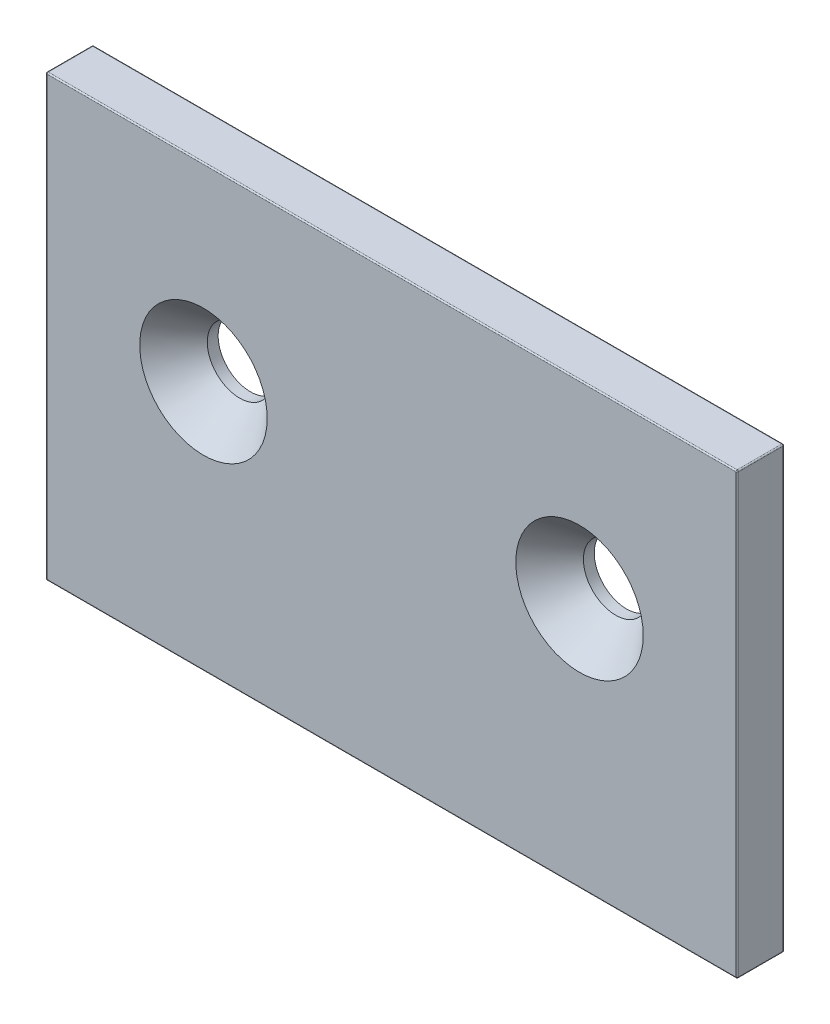
SolidWorks part; units mm, degrees
material "Chrome Stainless Steel"
ref_plane "Front Plane" through (0, 0, 0) normal (0, 0, 1) x (1, 0, 0)
ref_plane "Top Plane" through (0, 0, 0) normal (0, 1, 0) x (1, 0, 0)
ref_plane "Right Plane" through (0, 0, 0) normal (1, 0, 0) x (0, 0, -1)
sketch "Sketch1" plane through (0, 0, 0) normal (0, 0, 1) x (1, 0, 0)
  line L1 (-34.925, 0) -> (34.925, 0)
  line L2 (-34.925, 0) -> (-34.925, 44.45)
  line L3 (-34.925, 44.45) -> (34.925, 44.45)
  line L4 (34.925, 0) -> (34.925, 44.45)
  dimension "D1" = 69.85
  dimension "D2" = 44.45
extrude "Boss-Extrude1" add sketch "Sketch1" along normal mid plane 4.7498
hole_wizard "CSK for 1/4 Flat Head Machine Screw2" positions "3DSketch2" profile "Sketch4" countersink size "1/4" standard "ANSI Inch"
sketch3d "3DSketch2"
  line L0 (0, 0, 0) -> (0, 25.4, 0) construction
  line L2 (-34.925, 25.4, 2.3749) -> (34.925, 25.4, 2.3749) construction
  line L3 (-34.925, 44.45, 2.3749) -> (-34.925, 0, 2.3749) construction
  line L4 (34.925, 0, 2.3749) -> (34.925, 44.45, 2.3749) construction
  point P7 (18.9987, 25.3151, 2.3749)
  point P18 (-19.0469, 25.3882, 0.3417)
  point P20 (-19.0469, 25.3882, 0.3417)
  point P22 (0, 0, 0)
  point P23 (0, 0, 0)
  point P26 (0, 0, 0)
  point P29 (0, 0, 0)
  point P31 (0, 0, 0)
  point P32 (0, 0, 0)
  point P33 (0, 0, 0)
  point P34 (0, 0, 0)
  point P35 (0, 0, 0)
  dimension "D1" = 38.1
  dimension "D2" = 19.05
sketch "Sketch4" plane through (18.9987, 25.3151, 2.3749) normal (1, 0, 0) x (0, -1, 0)
  line L0 (0, 0) -> (0, 4.7498)
  line L1 (0, 4.7498) -> (3.2639, 4.7498)
  line L2 (3.2639, 4.7498) -> (3.2639, 3.6524)
  line L3 (3.2639, 3.6524) -> (6.4389, 0)
  line L5 (6.4389, 0) -> (0, 0)
  line L6 (-3.2639, 3.6524) -> (-6.4389, 0) construction
  line L11 (0, -6.35) -> (0, 107.95) construction
  dimension "Thru Hole Dia." = 6.5278
  dimension "Thru Hole Depth" = 4.7498
  dimension "Near C'Sink Dia." = 12.8778
  dimension "Near C'Sink Angle" = 82
mirror "Mirror1" about plane through (0, 0, 0) normal (1, 0, 0) of "CSK for 1/4 Flat Head Machine Screw2"
fillet "Fillet1" radius 0.127 12 edges at (0, 44.45, 2.3749) (0, 44.45, -2.3749) (-34.925, 44.45, 0) (-34.925, 22.225, 2.3749) (-34.925, 22.225, -2.3749) (-34.925, 0, 0) (0, 0, 2.3749) (0, 0, -2.3749) (34.925, 0, 0) (34.925, 22.225, 2.3749) (34.925, 44.45, 0) (34.925, 22.225, -2.3749)
